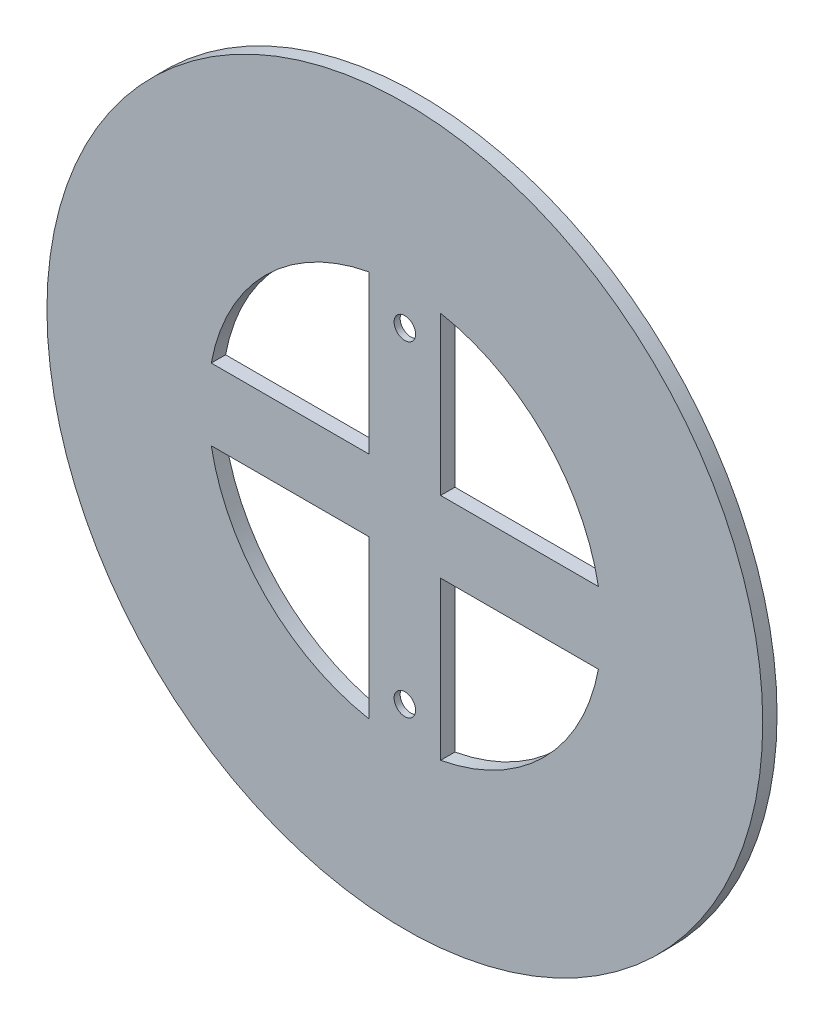
SolidWorks part; units mm, degrees
ref_plane "Front Plane" through (0, 0, 0) normal (0, 0, 1) x (1, 0, 0)
ref_plane "Top Plane" through (0, 0, 0) normal (0, 1, 0) x (1, 0, 0)
ref_plane "Right Plane" through (0, 0, 0) normal (1, 0, 0) x (0, 0, -1)
sketch "Sketch1" plane through (0, 0, 0) normal (0, 0, 1) x (1, 0, 0)
  circle A0 centre (0, 0) radius 50
  dimension "D1" = 100
extrude "Boss-Extrude1" add sketch "Sketch1" along normal blind 2
sketch "Sketch2" plane through (0, 0, 0) normal (0, 0, 1) x (1, 0, 0)
  circle A0 centre (0, 0) radius 36.25
  circle A1 centre (0, 0) radius 42.5
  dimension "D1" = 72.5
  dimension "D2" = 85
extrude "Cut-Extrude1" cut sketch "Sketch2" along normal blind 1
sketch "Sketch3" plane through (0, 0, 0) normal (0, 0, -1) x (-1, 0, 0)
  line L0 (-5, 27.0416) -> (-5, 5)
  line L1 (5, 27.0416) -> (5, 5)
  line L2 (27.0416, 5) -> (5, 5)
  line L3 (27.0416, -5) -> (5, -5)
  line L4 (5, -27.0416) -> (5, -5)
  line L5 (-5, -27.0416) -> (-5, -5)
  line L6 (-27.0416, -5) -> (-5, -5)
  line L7 (-27.0416, 5) -> (-5, 5)
  line L8 (0, 0) -> (-50000, 0) construction
  arc A0 (-5, 27.0416) -> (-27.0416, 5) centre (0, 0) ccw
  arc A1 (27.0416, 5) -> (5, 27.0416) centre (0, 0) ccw
  arc A2 (5, -27.0416) -> (27.0416, -5) centre (0, 0) ccw
  arc A3 (-27.0416, -5) -> (-5, -27.0416) centre (0, 0) ccw
  circle A4 centre (0, 22.75) radius 1.5
  circle A5 centre (0, -22.75) radius 1.5
  point P22 (0, 0)
  dimension "D1" = 55
  dimension "D4" = 22.75
  dimension "D5" = 3
  dimension "D2" = 10
  dimension "D3" = 4
extrude "Cut-Extrude2" cut sketch "Sketch3" against normal through all
chamfer "Chamfer1" distance 2 angle 30 2 edges at (1.5, -22.75, 0) (-1.5, 22.75, 0)
